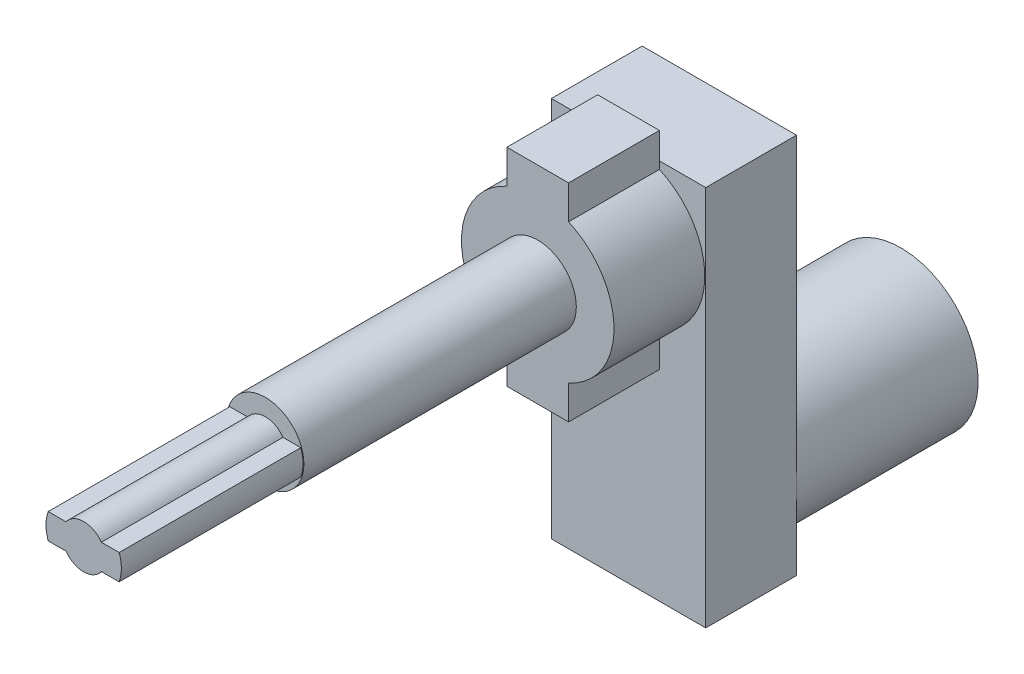
SolidWorks part; units mm, degrees
ref_plane "Front Plane" through (0, 0, 0) normal (0, 0, 1) x (1, 0, 0)
ref_plane "Top Plane" through (0, 0, 0) normal (0, 1, 0) x (1, 0, 0)
ref_plane "Right Plane" through (0, 0, 0) normal (1, 0, 0) x (0, 0, -1)
sketch "Sketch3" plane through (0, 0, 16) normal (0, 0, 1) x (1, 0, 0)
  circle A0 centre (0, 0) radius 4.25
  dimension "D1" = 8.5
extrude "Boss-Extrude2" add sketch "Sketch3" along normal blind 30 from offset 20 offset against normal yes
sketch "Sketch4" plane through (0, 0, -4) normal (0, 0, -1) x (-1, 0, 0)
  circle A0 centre (0, 0) radius 8.5
  dimension "D1" = 17
extrude "Boss-Extrude3" add sketch "Sketch4" along normal blind 10 from offset 10
sketch "Sketch5" plane through (0, 0, -24) normal (0, 0, -1) x (-1, 0, 0)
  line L1 (-8.5, 8.5) -> (8.5, 8.5)
  line L2 (-8.5, 8.5) -> (-8.5, -33.5)
  line L3 (-8.5, -33.5) -> (8.5, -33.5)
  line L4 (8.5, 8.5) -> (8.5, -33.5)
  circle A0 centre (0, 0) radius 8.5 construction
  circle A1 centre (0, -25) radius 8.5 construction
  dimension "D1" = 25
extrude "Boss-Extrude4" add sketch "Sketch5" against normal blind 10
sketch "Sketch6" plane through (0, 0, -24) normal (0, 0, -1) x (-1, 0, 0)
  line L0 (-8.5, -33.5) -> (8.5, -33.5) construction
  line L1 (-8.5, 8.5) -> (-8.5, -33.5) construction
  line L2 (8.5, -33.5) -> (8.5, 8.5) construction
  circle A0 centre (0, -25) radius 8.5
extrude "Boss-Extrude5" add sketch "Sketch6" along normal blind 20
sketch "Sketch9" plane through (0, 0, -44) normal (0, 0, -1) x (-1, 0, 0)
  line L1 (3.5, -28.5) -> (-3.5, -28.5)
  line L2 (3.5, -28.5) -> (3.5, -21.5)
  line L3 (3.5, -21.5) -> (-3.5, -21.5)
  line L4 (-3.5, -28.5) -> (-3.5, -21.5)
  line L5 (3.5, -28.5) -> (-3.5, -21.5) construction
  line L6 (3.5, -21.5) -> (-3.5, -28.5) construction
  arc A0 (8.5, -25) -> (-8.5, -25) centre (0, -25) ccw construction
  point P0 (0, -25)
  dimension "D1" = 7
  dimension "D2" = 7
extrude "Cut-Extrude1" cut sketch "Sketch9" against normal blind 20
sketch "Sketch11" plane through (0, 0, -14) normal (0, 0, 1) x (1, 0, 0)
  line L0 (3.4, -7.6811) -> (3.4, -11.4)
  line L1 (3.4, 11.4) -> (-3.4, 11.4)
  line L2 (3.4, 11.4) -> (3.4, 7.6811)
  line L3 (3.4, -11.4) -> (-3.4, -11.4)
  line L4 (-3.4, 11.4) -> (-3.4, 7.6811)
  line L5 (3.4, 11.4) -> (-3.4, -11.4) construction
  line L6 (3.4, -11.4) -> (-3.4, 11.4) construction
  line L7 (-3.4, -7.6811) -> (-3.4, -11.4)
  arc A0 (-3.4, 7.6811) -> (-3.4, -7.6811) centre (0, 0) ccw
  arc A1 (3.4, -7.6811) -> (3.4, 7.6811) centre (0, 0) ccw
  dimension "D3" = 16.8
  dimension "D1" = 6.8
  dimension "D2" = 22.8
extrude "Boss-Extrude7" add sketch "Sketch11" along normal blind 10
sketch "Sketch13" plane through (0, 0, 26) normal (0, 0, 1) x (1, 0, 0)
  line L0 (-1.9494, 1.4) -> (-3.9067, 1.4)
  line L1 (3.9067, -1.4) -> (1.9494, -1.4)
  line L3 (3.9067, 1.4) -> (1.9494, 1.4)
  line L5 (-1.9494, -1.4) -> (-3.9067, -1.4)
  line L6 (3.1895, 1.4) -> (3.1895, -1.4) construction
  arc A0 (3.9067, -1.4) -> (3.9067, 1.4) centre (0, 0) ccw
  arc A1 (-1.9494, -1.4) -> (1.9494, -1.4) centre (0, 0) ccw
  arc A2 (1.9494, 1.4) -> (-1.9494, 1.4) centre (0, 0) ccw
  arc A3 (-3.9067, 1.4) -> (-3.9067, -1.4) centre (0, 0) ccw
  point P1 (3.1895, 0)
  dimension "D1" = 4.8
  dimension "D3" = 8.3
  dimension "D2" = 2.8
extrude "Boss-Extrude8" add sketch "Sketch13" along normal blind 20
